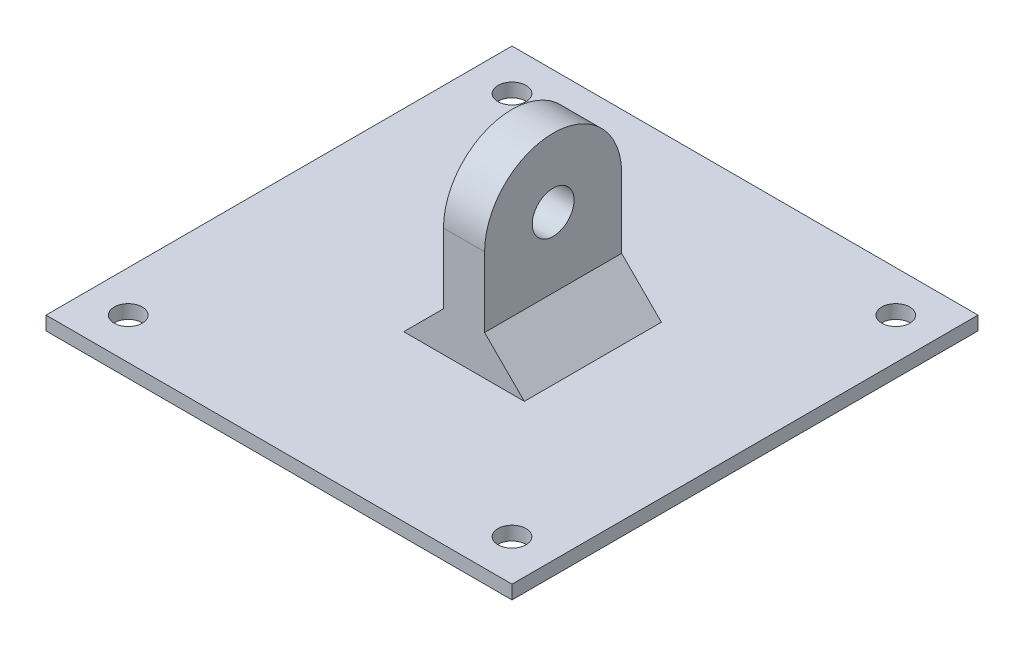
SolidWorks part; units mm, degrees
ref_plane "Front Plane" through (0, 0, 0) normal (0, 0, 1) x (1, 0, 0)
ref_plane "Top Plane" through (0, 0, 0) normal (0, 1, 0) x (1, 0, 0)
ref_plane "Right Plane" through (0, 0, 0) normal (1, 0, 0) x (0, 0, -1)
sketch "Sketch1" plane through (0, 0, 0) normal (0, 1, 0) x (1, 0, 0)
  line L1 (-17, -17) -> (17, -17)
  line L2 (-17, -17) -> (-17, 17)
  line L3 (-17, 17) -> (17, 17)
  line L4 (17, -17) -> (17, 17)
  line L5 (-17, -17) -> (17, 17) construction
  line L6 (-17, 17) -> (17, -17) construction
  circle A0 centre (-14, 14) radius 1.025
  circle A1 centre (14, 14) radius 1.025
  circle A2 centre (14, -14) radius 1.025
  circle A3 centre (-14, -14) radius 1.025
  point P0 (0, 0)
  dimension "D4" = 2.05
  dimension "D5" = 2
  dimension "D1" = 34
  dimension "D2" = 34
  dimension "D3" = 14
  dimension "D6" = 2
extrude "Boss-Extrude1" add sketch "Sketch1" along normal blind 1
sketch "Sketch4" plane through (0, 0, 0) normal (1, 0, 0) x (0, 0, -1)
  line L0 (-17, 1) -> (17, 1) construction
  line L1 (-5, 1) -> (5, 1)
  line L2 (-5, 1) -> (-5, 9)
  line L4 (5, 1) -> (5, 9)
  circle A0 centre (0, 9) radius 1.525
  arc A1 (-5, 9) -> (5, 9) centre (0, 9) cw
  dimension "D3" = 3.05
  dimension "D1" = 10
  dimension "D2" = 8
extrude "Boss-Extrude2" add sketch "Sketch4" along normal blind 3
chamfer "Chamfer1" distance 2.9 angle 45 2 edges at (0, 1, 0) (3, 1, 0)
